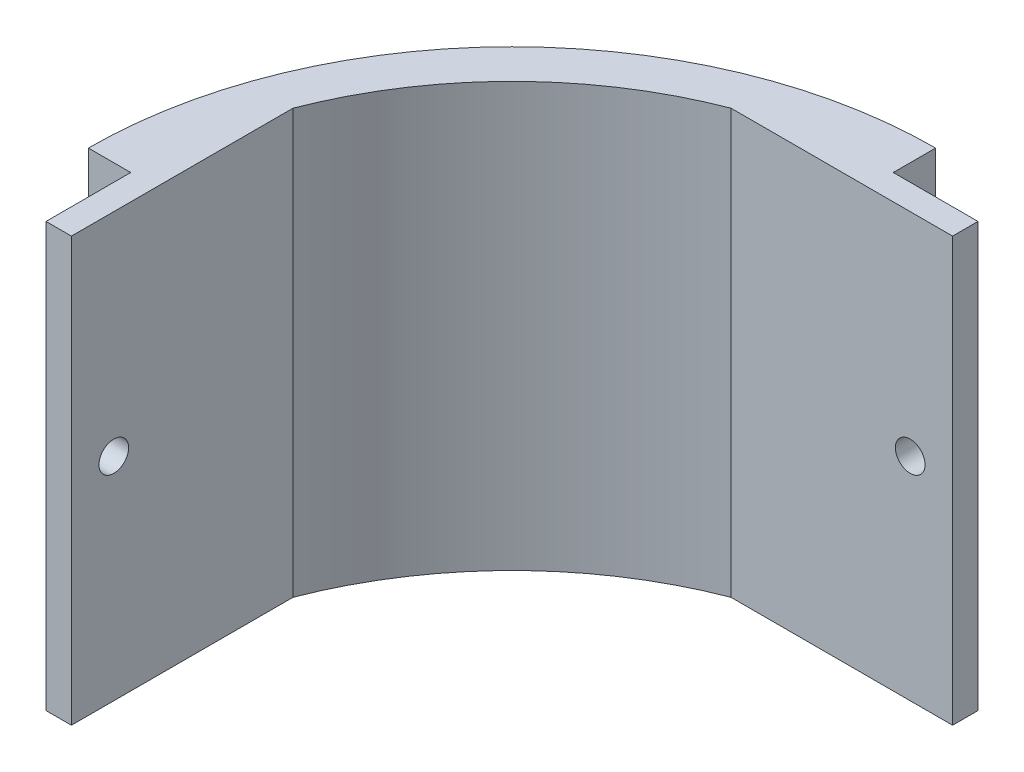
SolidWorks part; units mm, degrees
ref_plane "Front Plane" through (0, 0, 0) normal (0, 0, 1) x (1, 0, 0)
ref_plane "Top Plane" through (0, 0, 0) normal (0, 1, 0) x (1, 0, 0)
ref_plane "Right Plane" through (0, 0, 0) normal (1, 0, 0) x (0, 0, -1)
sketch "Sketch1" plane through (0, 0, 0) normal (0, 1, 0) x (1, 0, 0)
  line L0 (0, 0) -> (0, 50) construction
  line L1 (0, 0) -> (-50, 0) construction
  line L2 (-50, 0) -> (-45, 0)
  line L3 (0, 50) -> (0, 45)
  arc A0 (0, 50) -> (-50, 0) centre (0, 0) ccw
  arc A1 (0, 45) -> (-45, 0) centre (0, 0) ccw
  point P4 (-45, 0)
  point P5 (-50, 0)
  dimension "D1" = 100
  dimension "D2" = 5
extrude "Boss-Extrude1" add sketch "Sketch1" along normal blind 50
sketch "Sketch2" plane through (0, 0, 0) normal (0, 0, 1) x (1, 0, 0)
  line L0 (-50, 50) -> (-45, 50) construction
  line L1 (-45, 0) -> (-42, 0)
  line L2 (-45, 0) -> (-45, 50)
  line L3 (-45, 50) -> (-42, 50)
  line L4 (-42, 0) -> (-42, 50)
  dimension "D1" = 3
extrude "Boss-Extrude2" add sketch "Sketch2" along normal blind 10 and the other way up to next
sketch "Sketch4" plane through (0, 0, 0) normal (1, 0, 0) x (0, 0, -1)
  line L0 (16.1555, 0) -> (45, 0) construction
  line L1 (45, 50) -> (42, 50)
  line L2 (45, 50) -> (45, 0)
  line L3 (45, 0) -> (42, 0)
  line L4 (42, 50) -> (42, 0)
  dimension "D1" = 3
extrude "Boss-Extrude3" add sketch "Sketch4" along normal blind 10 and the other way up to next
sketch "Sketch5" plane through (0, 0, -45) normal (0, 0, -1) x (-1, 0, 0)
  line L1 (-10, 0) -> (-10, 50) construction
  circle A0 centre (-5, 25) radius 1.75
  point P2 (0, 0)
  point P5 (0, 0)
  point P8 (-10, 25)
  dimension "D1" = 3.5
  dimension "D2" = 5
extrude "Cut-Extrude1" cut sketch "Sketch5" against normal blind 10
sketch "Sketch6" plane through (-45, 0, 0) normal (-1, 0, 0) x (0, 0, 1)
  line L0 (10, 50) -> (10, 0) construction
  circle A0 centre (5, 25) radius 1.75
  point P2 (0, 0)
  point P5 (0, 0)
  point P6 (10, 25)
  dimension "D1" = 3.5
  dimension "D2" = 5
extrude "Cut-Extrude2" cut sketch "Sketch6" against normal blind 10
